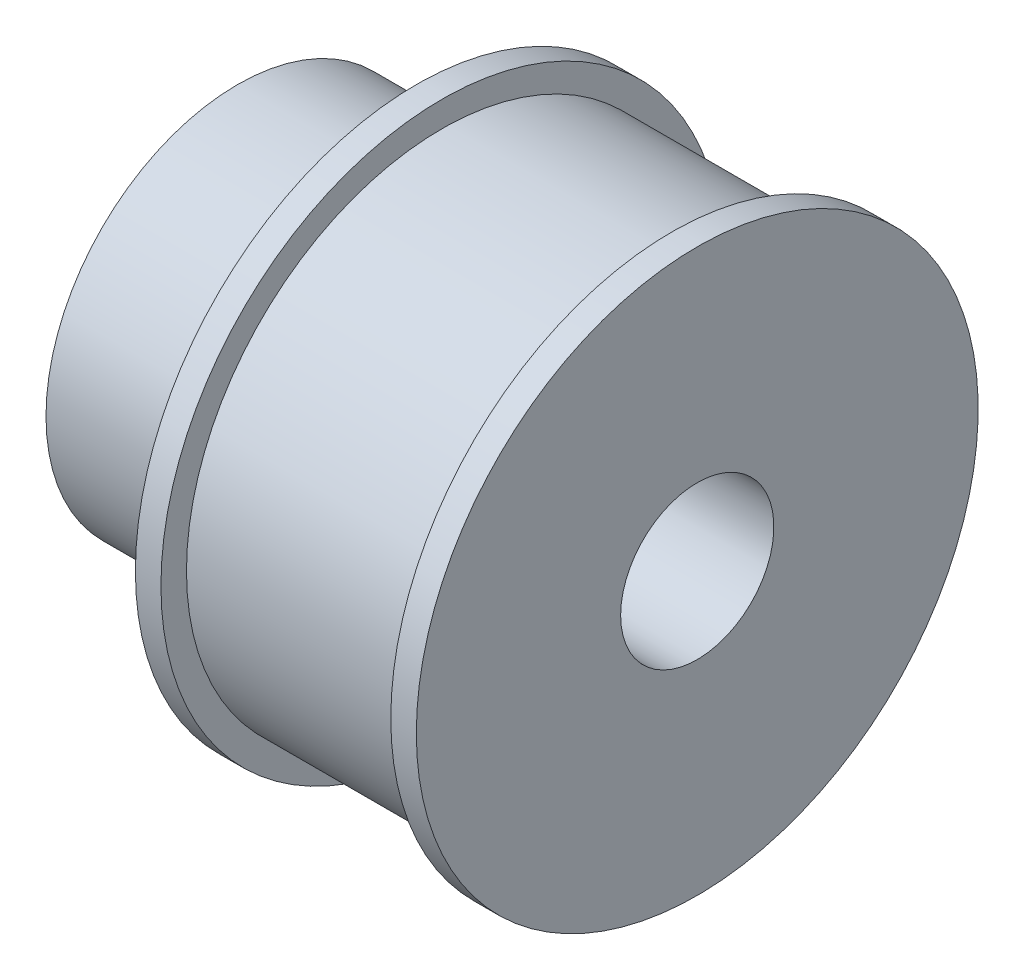
SolidWorks part; units mm, degrees
ref_plane "Front Plane" through (0, 0, 0) normal (0, 0, 1) x (1, 0, 0)
ref_plane "Top Plane" through (0, 0, 0) normal (0, 1, 0) x (1, 0, 0)
ref_plane "Right Plane" through (0, 0, 0) normal (1, 0, 0) x (0, 0, -1)
sketch "Sketch1" plane through (0, 0, 0) normal (0, 1, 0) x (1, 0, 0)
  line L0 (0, 3) -> (0, 7.5)
  line L1 (0, 7.5) -> (7, 7.5)
  line L2 (7, 7.5) -> (7, 11)
  line L3 (7, 11) -> (8, 11)
  line L4 (18, 11) -> (18, 3)
  line L5 (18, 3) -> (0, 3)
  line L6 (8, 11) -> (8, 10)
  line L7 (8, 10) -> (17, 10)
  line L8 (17, 10) -> (17, 11)
  line L9 (17, 11) -> (18, 11)
  line L10 (12.5, 17.4029) -> (12.5, 10.4549) construction
  line L11 (0, 0) -> (18, 0) construction
  dimension "D1" = 3
  dimension "D2" = 7.5
  dimension "D3" = 7
  dimension "D4" = 18
  dimension "D5" = 1
  dimension "D6" = 1
  dimension "D7" = 11
revolve "Revolve1" add sketch "Sketch1" angle 360 about L11
